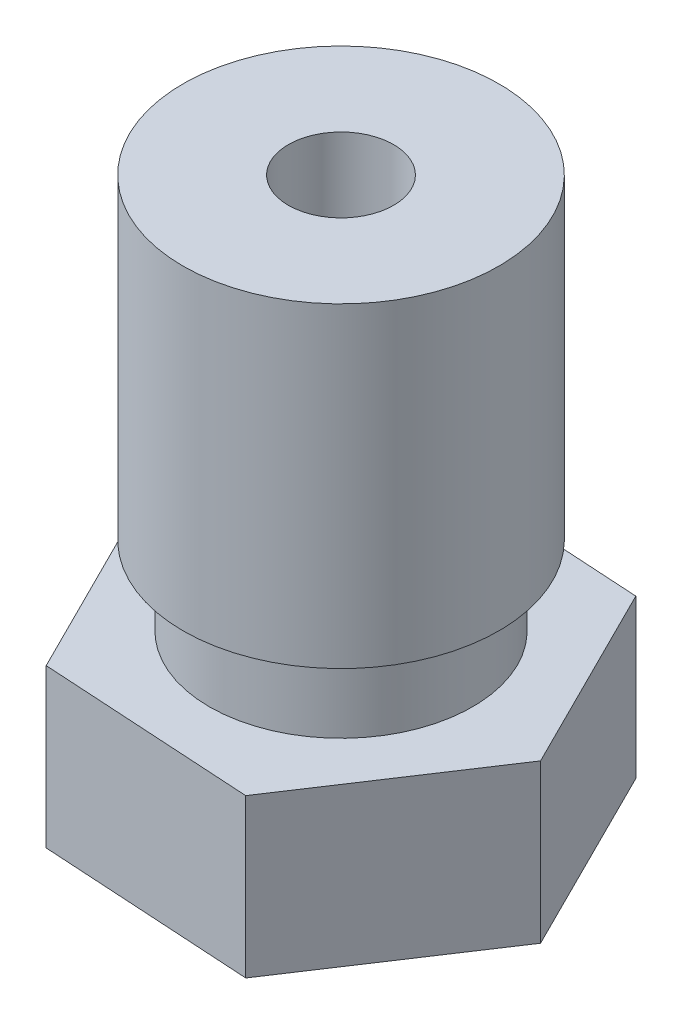
SolidWorks part; units mm, degrees
material "Mosaz"
ref_plane "Přední rovina" through (0, 0, 0) normal (0, 0, 1) x (1, 0, 0)
ref_plane "Horní rovina" through (0, 0, 0) normal (0, 1, 0) x (1, 0, 0)
ref_plane "Pravá rovina" through (0, 0, 0) normal (1, 0, 0) x (0, 0, -1)
sketch "Skica1" plane through (0, 0, 0) normal (0, 0, 1) x (1, 0, 0)
  line L0 (0, 5.8859) -> (0, -6.6141) construction
  line L1 (0, 5.8859) -> (1, 5.8859) construction
  line L2 (1, 5.8859) -> (3, 5.8859)
  line L3 (3, 5.8859) -> (3, -0.1141)
  line L4 (0, 5.8859) -> (0, -1.6141) construction
  line L5 (0, -1.6141) -> (2.5, -1.6141) construction
  line L6 (2.5, -1.6141) -> (2.5, -0.1141)
  line L7 (3, -0.1141) -> (2.5, -0.1141)
  line L8 (0, 5.8859) -> (0, -4.6141) construction
  line L9 (0, -2.8385) -> (3.5, -2.8385) construction
  line L10 (2.5, -1.6141) -> (3.5, -1.6141)
  line L11 (3.5, -1.6141) -> (3.5, -4.6141)
  line L12 (0, -6.6141) -> (0.315, -6.6141) construction
  line L13 (0.315, -6.6141) -> (3.1713, -4.6141)
  line L14 (3.1713, -4.6141) -> (3.5, -4.6141)
  line L15 (0, -6.6141) -> (0.15, -6.6141) construction
  line L16 (0.315, -6.6141) -> (0.15, -6.6141)
  line L17 (0, -6.6141) -> (0, -6.1141) construction
  line L18 (0, -6.1141) -> (0.5, -6.1141) construction
  line L19 (0.15, -6.6141) -> (0.15, -6.1141)
  line L20 (0.15, -6.1141) -> (0.5, -5.7641)
  line L21 (1, 5.8859) -> (1, -4.6141)
  line L22 (1, -4.6141) -> (0.5, -5.1141)
  line L23 (0.5, -5.1141) -> (0.5, -5.7641)
  dimension "D1" = 12.5
  dimension "D2" = 1
  dimension "D3" = 2
  dimension "D4" = 6
  dimension "D5" = 7.5
  dimension "D6" = 2.5
  dimension "D7" = 0.5
  dimension "D8" = 10.5
  dimension "D9" = 3.5
  dimension "D10" = 0.315
  dimension "D11" = 3
  dimension "D12" = 3.4869
  dimension "D13" = 0.3287
  dimension "D14" = 1
  dimension "D15" = 0.15
  dimension "D16" = 0.165
  dimension "D17" = 0.5
  dimension "D18" = 0.5
revolve "Rotovat1" add sketch "Skica1" angle 360 about L0
sketch "Skica2" plane through (0, -1.6141, 0) normal (0, 1, 0) x (1, 0, 0)
  line L1 (-4.0341, 0.2439) -> (-2.2283, -3.3717)
  line L2 (-2.2283, -3.3717) -> (1.8058, -3.6156)
  line L3 (1.8058, -3.6156) -> (4.0341, -0.2439)
  line L4 (4.0341, -0.2439) -> (2.2283, 3.3717)
  line L5 (2.2283, 3.3717) -> (-1.8058, 3.6156)
  line L6 (-1.8058, 3.6156) -> (-4.0341, 0.2439)
  circle A0 centre (0, 0) radius 3.5 construction
extrude "Přidat vysunutím1" add sketch "Skica2" against normal blind 3
sketch "Skica3" plane through (0, -1.6141, 0) normal (0, 1, 0) x (1, 0, 0)
  circle A0 centre (0, 0) radius 1
extrude "Odebrat vysunutím1" cut sketch "Skica3" against normal blind 3
